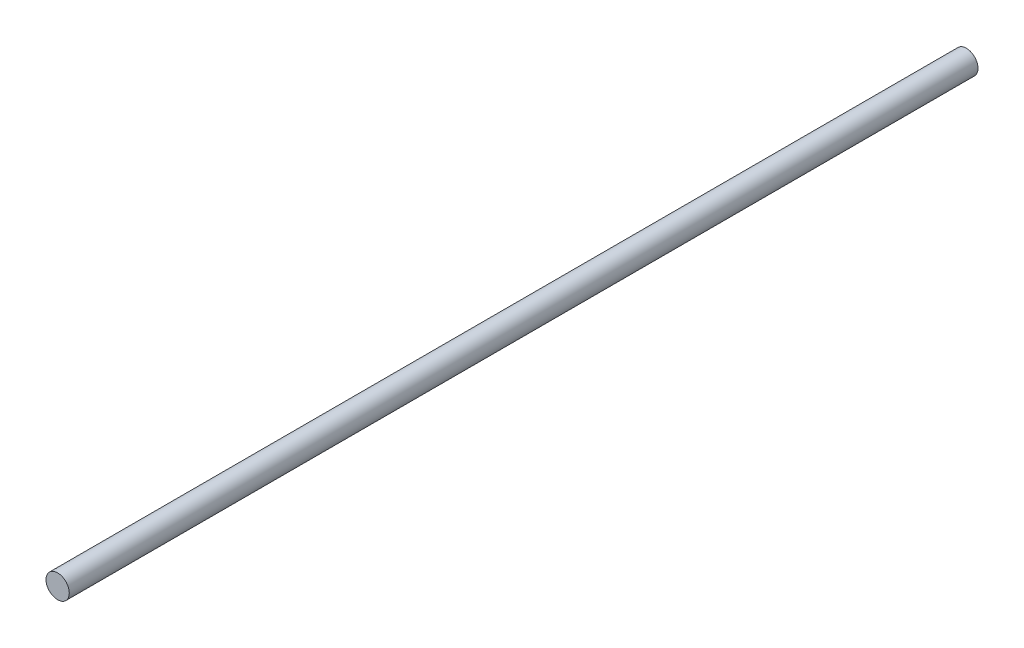
SolidWorks part; units mm, degrees
material "Unlegierter Baustahl"
ref_plane "Ebene vorne" through (0, 0, 0) normal (0, 0, 1) x (1, 0, 0)
ref_plane "Ebene oben" through (0, 0, 0) normal (0, 1, 0) x (1, 0, 0)
ref_plane "Ebene rechts" through (0, 0, 0) normal (1, 0, 0) x (0, 0, -1)
sketch "Skizze1" plane through (0, 0, 0) normal (0, 0, 1) x (1, 0, 0)
  circle A0 centre (-21.2024, 3.9585) radius 2.5
extrude "Aufsatz-Linear austragen1" add sketch "Skizze1" along normal blind 195
